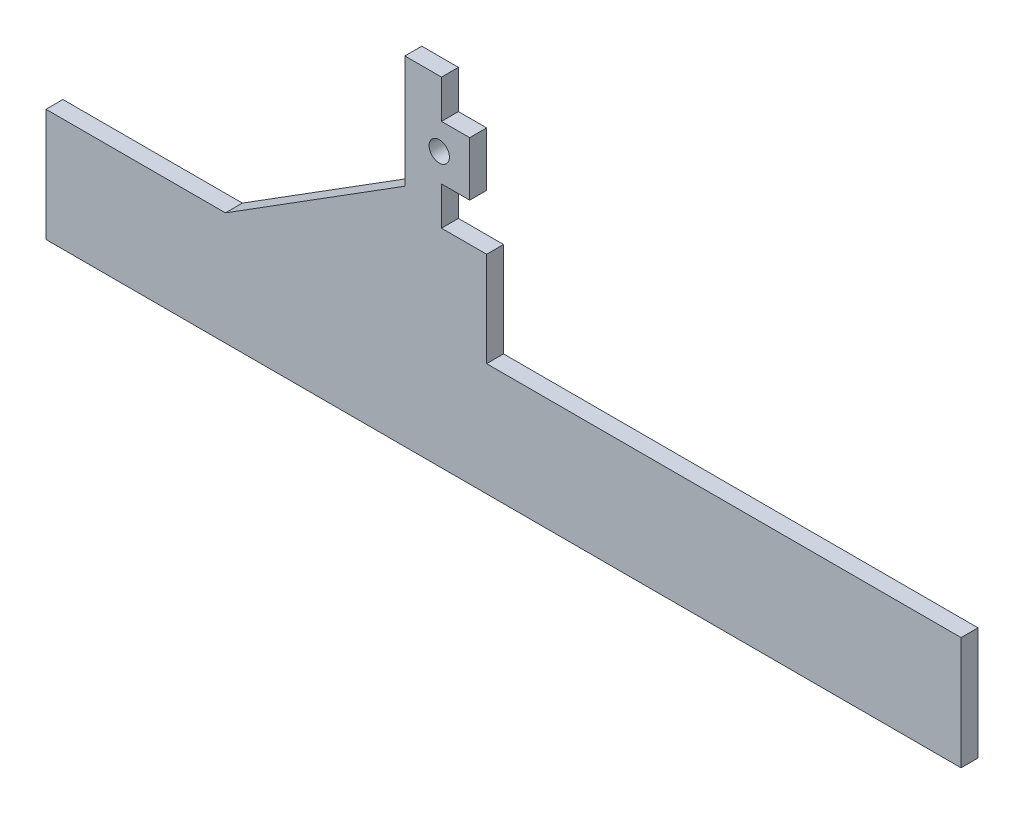
SolidWorks part; units mm, degrees
ref_plane "Alzado" through (0, 0, 0) normal (0, 0, 1) x (1, 0, 0)
ref_plane "Planta" through (0, 0, 0) normal (0, 1, 0) x (1, 0, 0)
ref_plane "Vista lateral" through (0, 0, 0) normal (1, 0, 0) x (0, 0, -1)
sketch "Croquis1" plane through (0, 0, 0) normal (0, 0, 1) x (1, 0, 0)
  line L0 (-15, 50) -> (-15, 134)
  line L1 (-405.6, -50) -> (405.6, -50)
  line L2 (-405.6, -50) -> (-405.6, 50)
  line L3 (-405.6, 50) -> (-246.54, 50)
  line L4 (405.6, -50) -> (405.6, 50)
  line L5 (-405.6, -50) -> (405.6, 50) construction
  line L6 (-405.6, 50) -> (405.6, -50) construction
  line L7 (-55, 250) -> (-87.48, 250)
  line L8 (-87.48, 250) -> (-87.48, 150)
  line L9 (-15, 50) -> (405.6, 50)
  line L10 (-87.48, 150) -> (-246.54, 50)
  line L11 (-246.54, 50) -> (-87.48, 50) construction
  line L12 (-87.48, 50) -> (-87.48, 150) construction
  line L13 (-30, 168) -> (-30, 216)
  line L16 (-30, 216) -> (-55, 216)
  line L17 (-55, 250) -> (-55, 216)
  line L18 (-15, 134) -> (-55, 134)
  line L20 (-30, 168) -> (-55, 168)
  line L21 (-55, 134) -> (-55, 168)
  circle A0 centre (-56.98, 192) radius 9
  point P0 (0, 0)
  dimension "D11" = 18
  dimension "D1" = 811.2
  dimension "D2" = 100
  dimension "D3" = 72.48
  dimension "D4" = 15
  dimension "D5" = 200
  dimension "D6" = 34
  dimension "D7" = 48
  dimension "D8" = 15
  dimension "D9" = 40
  dimension "D10" = 30.5
  dimension "D12" = 24
extrude "Saliente-Extruir1" add sketch "Croquis1" along normal blind 15
sketch "Croquis2" plane through (0, 0, 15) normal (0, 0, 1) x (1, 0, 0)
  line L0 (0, -50) -> (0, 50) construction
  line L3 (-405.6, -50) -> (405.6, -50) construction
  line L4 (405.6, 50) -> (-15, 50) construction
sketch "Croquis3" plane through (0, 50, 0) normal (0, 1, 0) x (1, 0, 0)
  line L0 (-326.07, -15) -> (-326.07, 0) construction
  line L1 (-246.54, -15) -> (-405.6, -15) construction
  line L2 (-246.54, 0) -> (-405.6, 0) construction
